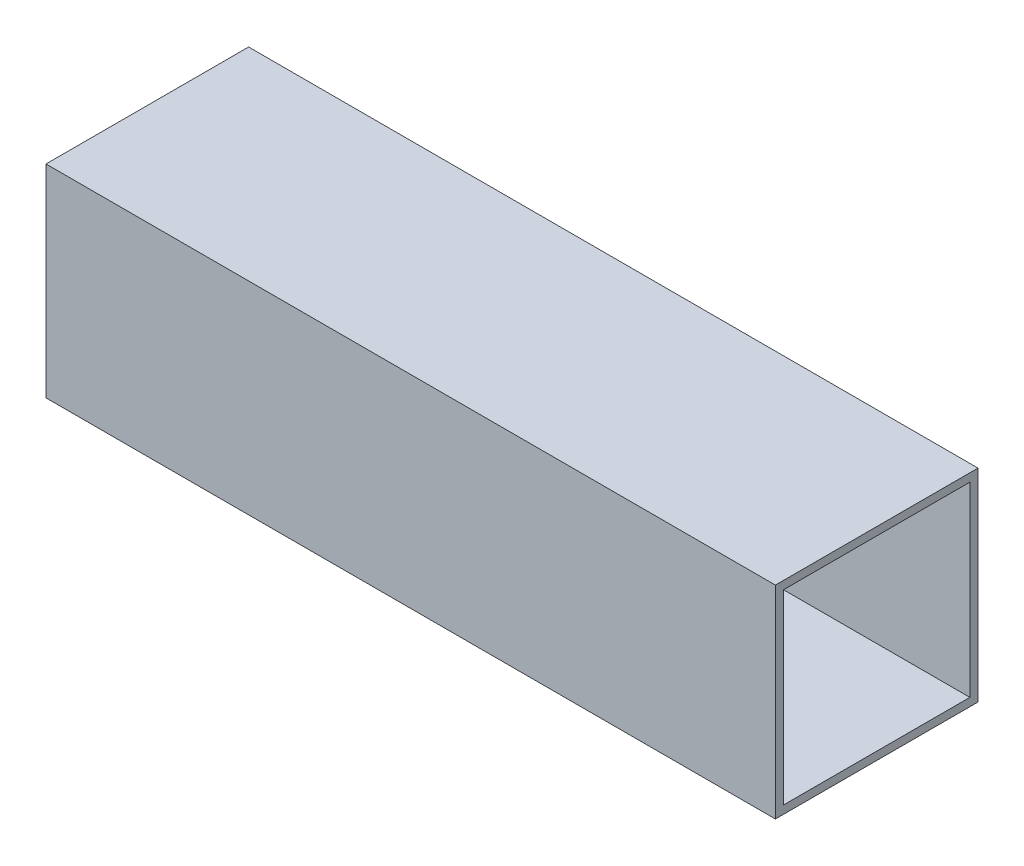
SolidWorks part; units mm, degrees
ref_plane "Front Plane" through (0, 0, 0) normal (0, 0, 1) x (1, 0, 0)
ref_plane "Top Plane" through (0, 0, 0) normal (0, 1, 0) x (1, 0, 0)
ref_plane "Right Plane" through (0, 0, 0) normal (1, 0, 0) x (0, 0, -1)
sketch "Sketch2" plane through (0, 0, 0) normal (0, 0, 1) x (1, 0, 0)
  line L1 (0, 0) -> (90, 0)
  line L2 (0, 0) -> (0, -25)
  line L3 (0, -25) -> (90, -25)
  line L4 (90, 0) -> (90, -25)
  dimension "D1" = 90
  dimension "D2" = 25
extrude "Boss-Extrude1" add sketch "Sketch2" along normal blind 25
sketch "Sketch3" plane through (90, 0, 0) normal (1, 0, 0) x (0, 0, -1)
  line L0 (-25, -25) -> (-25, 0) construction
  line L1 (-24, -24) -> (-1, -24)
  line L2 (-24, -24) -> (-24, -1)
  line L3 (-24, -1) -> (-1, -1)
  line L4 (-1, -24) -> (-1, -1)
  line L5 (-25, 0) -> (0, 0) construction
  line L12 (-24, -24) -> (-1, -1) construction
  line L13 (-24, -1) -> (-1, -24) construction
  line L14 (-25, -25) -> (0, -25) construction
  dimension "D1" = 1
  dimension "D2" = 1
  dimension "D3" = 1
extrude "Cut-Extrude1" cut sketch "Sketch3" against normal through all contours L2 L1 L4 L3
